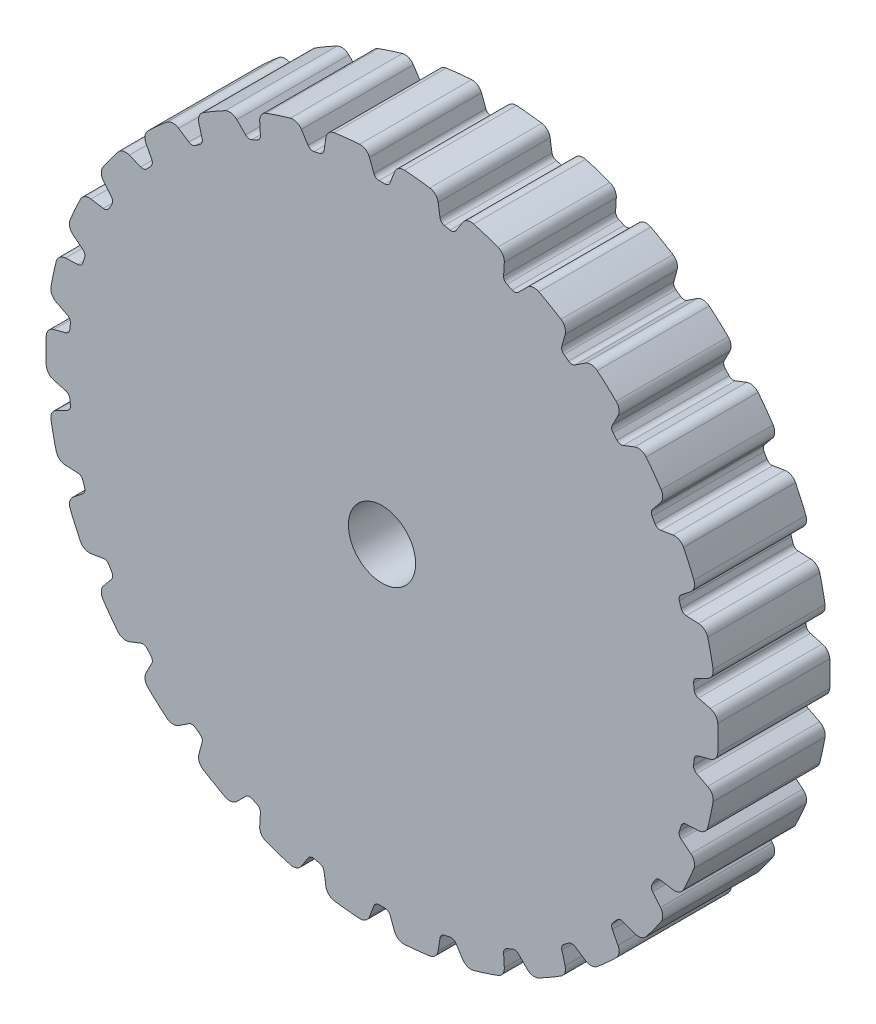
SolidWorks part; units mm, degrees
ref_plane "Front Plane" through (0, 0, 0) normal (0, 0, 1) x (1, 0, 0)
ref_plane "Top Plane" through (0, 0, 0) normal (0, 1, 0) x (1, 0, 0)
ref_plane "Right Plane" through (0, 0, 0) normal (1, 0, 0) x (0, 0, -1)
sketch "Sketch1" plane through (0, 0, 0) normal (0, 0, 1) x (1, 0, 0)
  circle A1 centre (0, 0) radius 38.1
  point P1 (0, 0)
extrude "Boss-Extrude1" add sketch "Sketch1" along normal blind 12.7
sketch "Sketch2" plane through (0, 0, 12.7) normal (0, 0, 1) x (1, 0, 0)
  circle A0 centre (0, 0) radius 3.81
extrude "Cut-Extrude1" cut sketch "Sketch2" against normal through all
sketch "Sketch3" plane through (0, 0, 12.7) normal (0, 0, 1) x (1, 0, 0)
  line L0 (0, 0) -> (0, 44.7155) construction
  line L1 (-1.4169, 37.2795) -> (-0.9223, 35.9705)
  line L2 (-0.3283, 35.56) -> (0.3283, 35.56)
  line L3 (1.4169, 37.2795) -> (0.9223, 35.9705)
  line L4 (7.0723, 34.8512) -> (7.7144, 34.7147)
  line L5 (9.1368, 36.1703) -> (8.3808, 34.9928)
  line L6 (6.3649, 36.7594) -> (6.5766, 35.3763)
  line L7 (14.1637, 32.6192) -> (14.7634, 32.3522)
  line L8 (16.4573, 33.4802) -> (15.4731, 32.4856)
  line L9 (13.8686, 34.6328) -> (13.788, 33.2358)
  line L10 (20.6361, 28.9616) -> (21.1672, 28.5757)
  line L11 (23.0586, 29.3269) -> (21.8891, 28.5587)
  line L12 (20.7661, 30.9926) -> (20.3968, 29.6429)
  line L13 (26.2066, 24.0382) -> (26.6459, 23.5503)
  line L14 (28.6521, 23.8919) -> (27.3484, 23.3836)
  line L15 (26.756, 25.9978) -> (26.1142, 24.7544)
  line L16 (30.6317, 18.0643) -> (30.96, 17.4957)
  line L17 (32.9934, 17.4127) -> (31.6125, 17.1866)
  line L18 (31.5765, 19.8668) -> (30.6903, 18.784)
  line L19 (33.7181, 11.3008) -> (33.921, 10.6765)
  line L20 (35.8927, 10.1725) -> (34.495, 10.2384)
  line L21 (35.0171, 12.8675) -> (33.925, 11.9926)
  line L22 (35.3309, 4.0435) -> (35.3995, 3.3906)
  line L23 (37.2234, 2.4877) -> (35.8699, 2.8427)
  line L24 (36.9272, 5.3059) -> (35.6771, 4.6772)
  line L25 (35.3995, -3.3906) -> (35.3309, -4.0435)
  line L26 (36.9272, -5.3059) -> (35.6771, -4.6772)
  line L27 (37.2234, -2.4877) -> (35.8699, -2.8427)
  line L28 (33.921, -10.6765) -> (33.7181, -11.3008)
  line L29 (35.0171, -12.8675) -> (33.925, -11.9926)
  line L30 (35.8927, -10.1725) -> (34.495, -10.2384)
  line L31 (30.96, -17.4957) -> (30.6317, -18.0643)
  line L32 (31.5765, -19.8668) -> (30.6903, -18.784)
  line L33 (32.9934, -17.4127) -> (31.6125, -17.1866)
  line L34 (26.6459, -23.5503) -> (26.2066, -24.0382)
  line L35 (26.756, -25.9978) -> (26.1142, -24.7544)
  line L36 (28.6521, -23.8919) -> (27.3484, -23.3836)
  line L37 (21.1672, -28.5757) -> (20.6361, -28.9616)
  line L38 (20.7661, -30.9926) -> (20.3968, -29.6429)
  line L39 (23.0586, -29.3269) -> (21.8891, -28.5587)
  line L40 (14.7634, -32.3522) -> (14.1637, -32.6192)
  line L41 (13.8686, -34.6328) -> (13.788, -33.2358)
  line L42 (16.4573, -33.4802) -> (15.4731, -32.4856)
  line L43 (7.7144, -34.7147) -> (7.0723, -34.8512)
  line L44 (6.3649, -36.7594) -> (6.5766, -35.3763)
  line L45 (9.1368, -36.1703) -> (8.3808, -34.9928)
  line L46 (0.3283, -35.56) -> (-0.3283, -35.56)
  line L47 (-1.4169, -37.2795) -> (-0.9223, -35.9705)
  line L48 (1.4169, -37.2795) -> (0.9223, -35.9705)
  line L49 (-7.0723, -34.8512) -> (-7.7144, -34.7147)
  line L50 (-9.1368, -36.1703) -> (-8.3808, -34.9928)
  line L51 (-6.3649, -36.7594) -> (-6.5766, -35.3763)
  line L52 (-14.1637, -32.6192) -> (-14.7634, -32.3522)
  line L53 (-16.4573, -33.4802) -> (-15.4731, -32.4856)
  line L54 (-13.8686, -34.6328) -> (-13.788, -33.2358)
  line L55 (-20.6361, -28.9616) -> (-21.1672, -28.5757)
  line L56 (-23.0586, -29.3269) -> (-21.8891, -28.5587)
  line L57 (-20.7661, -30.9926) -> (-20.3968, -29.6429)
  line L58 (-26.2066, -24.0382) -> (-26.6459, -23.5503)
  line L59 (-28.6521, -23.8919) -> (-27.3484, -23.3836)
  line L60 (-26.756, -25.9978) -> (-26.1142, -24.7544)
  line L61 (-30.6317, -18.0643) -> (-30.96, -17.4957)
  line L62 (-32.9934, -17.4127) -> (-31.6125, -17.1866)
  line L63 (-31.5765, -19.8668) -> (-30.6903, -18.784)
  line L64 (-33.7181, -11.3008) -> (-33.921, -10.6765)
  line L65 (-35.8927, -10.1725) -> (-34.495, -10.2384)
  line L66 (-35.0171, -12.8675) -> (-33.925, -11.9926)
  line L67 (-35.3309, -4.0435) -> (-35.3995, -3.3906)
  line L68 (-37.2234, -2.4877) -> (-35.8699, -2.8427)
  line L69 (-36.9272, -5.3059) -> (-35.6771, -4.6772)
  line L70 (-35.3995, 3.3906) -> (-35.3309, 4.0435)
  line L71 (-36.9272, 5.3059) -> (-35.6771, 4.6772)
  line L72 (-37.2234, 2.4877) -> (-35.8699, 2.8427)
  line L73 (-33.921, 10.6765) -> (-33.7181, 11.3008)
  line L74 (-35.0171, 12.8675) -> (-33.925, 11.9926)
  line L75 (-35.8927, 10.1725) -> (-34.495, 10.2384)
  line L76 (-30.96, 17.4957) -> (-30.6317, 18.0643)
  line L77 (-31.5765, 19.8668) -> (-30.6903, 18.784)
  line L78 (-32.9934, 17.4127) -> (-31.6125, 17.1866)
  line L79 (-26.6459, 23.5503) -> (-26.2066, 24.0382)
  line L80 (-26.756, 25.9978) -> (-26.1142, 24.7544)
  line L81 (-28.6521, 23.8919) -> (-27.3484, 23.3836)
  line L82 (-21.1672, 28.5757) -> (-20.6361, 28.9616)
  line L83 (-20.7661, 30.9926) -> (-20.3968, 29.6429)
  line L84 (-23.0586, 29.3269) -> (-21.8891, 28.5587)
  line L85 (-14.7634, 32.3522) -> (-14.1637, 32.6192)
  line L86 (-13.8686, 34.6328) -> (-13.788, 33.2358)
  line L87 (-16.4573, 33.4802) -> (-15.4731, 32.4856)
  line L88 (-7.7144, 34.7147) -> (-7.0723, 34.8512)
  line L89 (-6.3649, 36.7594) -> (-6.5766, 35.3763)
  line L90 (-9.1368, 36.1703) -> (-8.3808, 34.9928)
  circle A0 centre (0, 0) radius 38.1 construction
  arc A1 (-0.9223, 35.9705) -> (-0.3283, 35.56) centre (-0.3283, 36.195) ccw
  arc A2 (-2.54, 38.0152) -> (2.54, 38.0152) centre (0, 0) cw
  arc A3 (-1.4169, 37.2795) -> (-2.54, 38.0152) centre (-2.4834, 36.8765) ccw
  arc A4 (0.9223, 35.9705) -> (0.3283, 35.56) centre (0.3283, 36.195) cw
  arc A5 (1.4169, 37.2795) -> (2.54, 38.0152) centre (2.4834, 36.8765) cw
  arc A6 (8.3808, 34.9928) -> (7.7144, 34.7147) centre (7.8465, 35.3358) cw
  arc A7 (9.1368, 36.1703) -> (10.3883, 36.6564) centre (10.0962, 35.5543) cw
  arc A8 (5.4193, 37.7126) -> (10.3883, 36.6564) centre (0, 0) cw
  arc A9 (6.3649, 36.7594) -> (5.4193, 37.7126) centre (5.2379, 36.587) ccw
  arc A10 (6.5766, 35.3763) -> (7.0723, 34.8512) centre (7.2043, 35.4723) ccw
  arc A11 (15.4731, 32.4856) -> (14.7634, 32.3522) centre (15.0217, 32.9323) cw
  arc A12 (16.4573, 33.4802) -> (17.7826, 33.6955) centre (17.2678, 32.6782) cw
  arc A13 (13.1418, 35.7618) -> (17.7826, 33.6955) centre (0, 0) cw
  arc A14 (13.8686, 34.6328) -> (13.1418, 35.7618) centre (12.7303, 34.6984) ccw
  arc A15 (13.788, 33.2358) -> (14.1637, 32.6192) centre (14.422, 33.1993) ccw
  arc A16 (21.8891, 28.5587) -> (21.1672, 28.5757) centre (21.5405, 29.0894) cw
  arc A17 (23.0586, 29.3269) -> (24.3997, 29.262) centre (23.6846, 28.374) cw
  arc A18 (20.2899, 32.2479) -> (24.3997, 29.262) centre (0, 0) cw
  arc A19 (20.7661, 30.9926) -> (20.2899, 32.2479) centre (19.6663, 31.2934) ccw
  arc A20 (20.3968, 29.6429) -> (20.6361, 28.9616) centre (21.0093, 29.4753) ccw
  arc A21 (27.3484, 23.3836) -> (26.6459, 23.5503) centre (27.1178, 23.9752) cw
  arc A22 (28.6521, 23.8919) -> (29.9504, 23.5496) centre (29.0663, 22.8296) cw
  arc A23 (26.5512, 27.3247) -> (29.9504, 23.5496) centre (0, 0) cw
  arc A24 (26.756, 25.9978) -> (26.5512, 27.3247) centre (25.7428, 26.5207) ccw
  arc A25 (26.1142, 24.7544) -> (26.2066, 24.0382) centre (26.6785, 24.4631) ccw
  arc A26 (31.6125, 17.1866) -> (30.96, 17.4957) centre (31.5099, 17.8132) cw
  arc A27 (32.9934, 17.4127) -> (34.1922, 16.8079) centre (33.1777, 16.2875) cw
  arc A28 (31.6522, 21.2073) -> (34.1922, 16.8079) centre (0, 0) cw
  arc A29 (31.5765, 19.8668) -> (31.6522, 21.2073) centre (30.6942, 20.589) ccw
  arc A30 (30.6903, 18.784) -> (30.6317, 18.0643) centre (31.1817, 18.3818) ccw
  arc A31 (34.495, 10.2384) -> (33.921, 10.6765) centre (34.5249, 10.8727) cw
  arc A32 (35.8927, 10.1725) -> (36.9395, 9.3317) centre (35.839, 9.0336) cw
  arc A33 (35.3697, 14.163) -> (36.9395, 9.3317) centre (0, 0) cw
  arc A34 (35.0171, 12.8675) -> (35.3697, 14.163) centre (34.3042, 13.7574) ccw
  arc A35 (33.925, 11.9926) -> (33.7181, 11.3008) centre (34.3221, 11.4971) ccw
  arc A36 (35.8699, 2.8427) -> (35.3995, 3.3906) centre (36.031, 3.4569) cw
  arc A37 (37.2234, 2.4877) -> (38.0725, 1.4476) centre (36.934, 1.3848) cw
  arc A38 (37.5415, 6.4998) -> (38.0725, 1.4476) centre (0, 0) cw
  arc A39 (36.9272, 5.3059) -> (37.5415, 6.4998) centre (36.4149, 6.3245) ccw
  arc A40 (35.6771, 4.6772) -> (35.3309, 4.0435) centre (35.9624, 4.1099) ccw
  arc A41 (35.6771, -4.6772) -> (35.3309, -4.0435) centre (35.9624, -4.1099) cw
  arc A42 (36.9272, -5.3059) -> (37.5415, -6.4998) centre (36.4149, -6.3245) cw
  arc A43 (38.0725, -1.4476) -> (37.5415, -6.4998) centre (0, 0) cw
  arc A44 (37.2234, -2.4877) -> (38.0725, -1.4476) centre (36.934, -1.3848) ccw
  arc A45 (35.8699, -2.8427) -> (35.3995, -3.3906) centre (36.031, -3.4569) ccw
  arc A46 (33.925, -11.9926) -> (33.7181, -11.3008) centre (34.3221, -11.4971) cw
  arc A47 (35.0171, -12.8675) -> (35.3697, -14.163) centre (34.3042, -13.7574) cw
  arc A48 (36.9395, -9.3317) -> (35.3697, -14.163) centre (0, 0) cw
  arc A49 (35.8927, -10.1725) -> (36.9395, -9.3317) centre (35.839, -9.0336) ccw
  arc A50 (34.495, -10.2384) -> (33.921, -10.6765) centre (34.5249, -10.8727) ccw
  arc A51 (30.6903, -18.784) -> (30.6317, -18.0643) centre (31.1817, -18.3818) cw
  arc A52 (31.5765, -19.8668) -> (31.6522, -21.2073) centre (30.6942, -20.589) cw
  arc A53 (34.1922, -16.8079) -> (31.6522, -21.2073) centre (0, 0) cw
  arc A54 (32.9934, -17.4127) -> (34.1922, -16.8079) centre (33.1777, -16.2875) ccw
  arc A55 (31.6125, -17.1866) -> (30.96, -17.4957) centre (31.5099, -17.8132) ccw
  arc A56 (26.1142, -24.7544) -> (26.2066, -24.0382) centre (26.6785, -24.4631) cw
  arc A57 (26.756, -25.9978) -> (26.5512, -27.3247) centre (25.7428, -26.5207) cw
  arc A58 (29.9504, -23.5496) -> (26.5512, -27.3247) centre (0, 0) cw
  arc A59 (28.6521, -23.8919) -> (29.9504, -23.5496) centre (29.0663, -22.8296) ccw
  arc A60 (27.3484, -23.3836) -> (26.6459, -23.5503) centre (27.1178, -23.9752) ccw
  arc A61 (20.3968, -29.6429) -> (20.6361, -28.9616) centre (21.0093, -29.4753) cw
  arc A62 (20.7661, -30.9926) -> (20.2899, -32.2479) centre (19.6663, -31.2934) cw
  arc A63 (24.3997, -29.262) -> (20.2899, -32.2479) centre (0, 0) cw
  arc A64 (23.0586, -29.3269) -> (24.3997, -29.262) centre (23.6846, -28.374) ccw
  arc A65 (21.8891, -28.5587) -> (21.1672, -28.5757) centre (21.5405, -29.0894) ccw
  arc A66 (13.788, -33.2358) -> (14.1637, -32.6192) centre (14.422, -33.1993) cw
  arc A67 (13.8686, -34.6328) -> (13.1418, -35.7618) centre (12.7303, -34.6984) cw
  arc A68 (17.7826, -33.6955) -> (13.1418, -35.7618) centre (0, 0) cw
  arc A69 (16.4573, -33.4802) -> (17.7826, -33.6955) centre (17.2678, -32.6782) ccw
  arc A70 (15.4731, -32.4856) -> (14.7634, -32.3522) centre (15.0217, -32.9323) ccw
  arc A71 (6.5766, -35.3763) -> (7.0723, -34.8512) centre (7.2043, -35.4723) cw
  arc A72 (6.3649, -36.7594) -> (5.4193, -37.7126) centre (5.2379, -36.587) cw
  arc A73 (10.3883, -36.6564) -> (5.4193, -37.7126) centre (0, 0) cw
  arc A74 (9.1368, -36.1703) -> (10.3883, -36.6564) centre (10.0962, -35.5543) ccw
  arc A75 (8.3808, -34.9928) -> (7.7144, -34.7147) centre (7.8465, -35.3358) ccw
  arc A76 (-0.9223, -35.9705) -> (-0.3283, -35.56) centre (-0.3283, -36.195) cw
  arc A77 (-1.4169, -37.2795) -> (-2.54, -38.0152) centre (-2.4834, -36.8765) cw
  arc A78 (2.54, -38.0152) -> (-2.54, -38.0152) centre (0, 0) cw
  arc A79 (1.4169, -37.2795) -> (2.54, -38.0152) centre (2.4834, -36.8765) ccw
  arc A80 (0.9223, -35.9705) -> (0.3283, -35.56) centre (0.3283, -36.195) ccw
  arc A81 (-8.3808, -34.9928) -> (-7.7144, -34.7147) centre (-7.8465, -35.3358) cw
  arc A82 (-9.1368, -36.1703) -> (-10.3883, -36.6564) centre (-10.0962, -35.5543) cw
  arc A83 (-5.4193, -37.7126) -> (-10.3883, -36.6564) centre (0, 0) cw
  arc A84 (-6.3649, -36.7594) -> (-5.4193, -37.7126) centre (-5.2379, -36.587) ccw
  arc A85 (-6.5766, -35.3763) -> (-7.0723, -34.8512) centre (-7.2043, -35.4723) ccw
  arc A86 (-15.4731, -32.4856) -> (-14.7634, -32.3522) centre (-15.0217, -32.9323) cw
  arc A87 (-16.4573, -33.4802) -> (-17.7826, -33.6955) centre (-17.2678, -32.6782) cw
  arc A88 (-13.1418, -35.7618) -> (-17.7826, -33.6955) centre (0, 0) cw
  arc A89 (-13.8686, -34.6328) -> (-13.1418, -35.7618) centre (-12.7303, -34.6984) ccw
  arc A90 (-13.788, -33.2358) -> (-14.1637, -32.6192) centre (-14.422, -33.1993) ccw
  arc A91 (-21.8891, -28.5587) -> (-21.1672, -28.5757) centre (-21.5405, -29.0894) cw
  arc A92 (-23.0586, -29.3269) -> (-24.3997, -29.262) centre (-23.6846, -28.374) cw
  arc A93 (-20.2899, -32.2479) -> (-24.3997, -29.262) centre (0, 0) cw
  arc A94 (-20.7661, -30.9926) -> (-20.2899, -32.2479) centre (-19.6663, -31.2934) ccw
  arc A95 (-20.3968, -29.6429) -> (-20.6361, -28.9616) centre (-21.0093, -29.4753) ccw
  arc A96 (-27.3484, -23.3836) -> (-26.6459, -23.5503) centre (-27.1178, -23.9752) cw
  arc A97 (-28.6521, -23.8919) -> (-29.9504, -23.5496) centre (-29.0663, -22.8296) cw
  arc A98 (-26.5512, -27.3247) -> (-29.9504, -23.5496) centre (0, 0) cw
  arc A99 (-26.756, -25.9978) -> (-26.5512, -27.3247) centre (-25.7428, -26.5207) ccw
  arc A100 (-26.1142, -24.7544) -> (-26.2066, -24.0382) centre (-26.6785, -24.4631) ccw
  arc A101 (-31.6125, -17.1866) -> (-30.96, -17.4957) centre (-31.5099, -17.8132) cw
  arc A102 (-32.9934, -17.4127) -> (-34.1922, -16.8079) centre (-33.1777, -16.2875) cw
  arc A103 (-31.6522, -21.2073) -> (-34.1922, -16.8079) centre (0, 0) cw
  arc A104 (-31.5765, -19.8668) -> (-31.6522, -21.2073) centre (-30.6942, -20.589) ccw
  arc A105 (-30.6903, -18.784) -> (-30.6317, -18.0643) centre (-31.1817, -18.3818) ccw
  arc A106 (-34.495, -10.2384) -> (-33.921, -10.6765) centre (-34.5249, -10.8727) cw
  arc A107 (-35.8927, -10.1725) -> (-36.9395, -9.3317) centre (-35.839, -9.0336) cw
  arc A108 (-35.3697, -14.163) -> (-36.9395, -9.3317) centre (0, 0) cw
  arc A109 (-35.0171, -12.8675) -> (-35.3697, -14.163) centre (-34.3042, -13.7574) ccw
  arc A110 (-33.925, -11.9926) -> (-33.7181, -11.3008) centre (-34.3221, -11.4971) ccw
  arc A111 (-35.8699, -2.8427) -> (-35.3995, -3.3906) centre (-36.031, -3.4569) cw
  arc A112 (-37.2234, -2.4877) -> (-38.0725, -1.4476) centre (-36.934, -1.3848) cw
  arc A113 (-37.5415, -6.4998) -> (-38.0725, -1.4476) centre (0, 0) cw
  arc A114 (-36.9272, -5.3059) -> (-37.5415, -6.4998) centre (-36.4149, -6.3245) ccw
  arc A115 (-35.6771, -4.6772) -> (-35.3309, -4.0435) centre (-35.9624, -4.1099) ccw
  arc A116 (-35.6771, 4.6772) -> (-35.3309, 4.0435) centre (-35.9624, 4.1099) cw
  arc A117 (-36.9272, 5.3059) -> (-37.5415, 6.4998) centre (-36.4149, 6.3245) cw
  arc A118 (-38.0725, 1.4476) -> (-37.5415, 6.4998) centre (0, 0) cw
  arc A119 (-37.2234, 2.4877) -> (-38.0725, 1.4476) centre (-36.934, 1.3848) ccw
  arc A120 (-35.8699, 2.8427) -> (-35.3995, 3.3906) centre (-36.031, 3.4569) ccw
  arc A121 (-33.925, 11.9926) -> (-33.7181, 11.3008) centre (-34.3221, 11.4971) cw
  arc A122 (-35.0171, 12.8675) -> (-35.3697, 14.163) centre (-34.3042, 13.7574) cw
  arc A123 (-36.9395, 9.3317) -> (-35.3697, 14.163) centre (0, 0) cw
  arc A124 (-35.8927, 10.1725) -> (-36.9395, 9.3317) centre (-35.839, 9.0336) ccw
  arc A125 (-34.495, 10.2384) -> (-33.921, 10.6765) centre (-34.5249, 10.8727) ccw
  arc A126 (-30.6903, 18.784) -> (-30.6317, 18.0643) centre (-31.1817, 18.3818) cw
  arc A127 (-31.5765, 19.8668) -> (-31.6522, 21.2073) centre (-30.6942, 20.589) cw
  arc A128 (-34.1922, 16.8079) -> (-31.6522, 21.2073) centre (0, 0) cw
  arc A129 (-32.9934, 17.4127) -> (-34.1922, 16.8079) centre (-33.1777, 16.2875) ccw
  arc A130 (-31.6125, 17.1866) -> (-30.96, 17.4957) centre (-31.5099, 17.8132) ccw
  arc A131 (-26.1142, 24.7544) -> (-26.2066, 24.0382) centre (-26.6785, 24.4631) cw
  arc A132 (-26.756, 25.9978) -> (-26.5512, 27.3247) centre (-25.7428, 26.5207) cw
  arc A133 (-29.9504, 23.5496) -> (-26.5512, 27.3247) centre (0, 0) cw
  arc A134 (-28.6521, 23.8919) -> (-29.9504, 23.5496) centre (-29.0663, 22.8296) ccw
  arc A135 (-27.3484, 23.3836) -> (-26.6459, 23.5503) centre (-27.1178, 23.9752) ccw
  arc A136 (-20.3968, 29.6429) -> (-20.6361, 28.9616) centre (-21.0093, 29.4753) cw
  arc A137 (-20.7661, 30.9926) -> (-20.2899, 32.2479) centre (-19.6663, 31.2934) cw
  arc A138 (-24.3997, 29.262) -> (-20.2899, 32.2479) centre (0, 0) cw
  arc A139 (-23.0586, 29.3269) -> (-24.3997, 29.262) centre (-23.6846, 28.374) ccw
  arc A140 (-21.8891, 28.5587) -> (-21.1672, 28.5757) centre (-21.5405, 29.0894) ccw
  arc A141 (-13.788, 33.2358) -> (-14.1637, 32.6192) centre (-14.422, 33.1993) cw
  arc A142 (-13.8686, 34.6328) -> (-13.1418, 35.7618) centre (-12.7303, 34.6984) cw
  arc A143 (-17.7826, 33.6955) -> (-13.1418, 35.7618) centre (0, 0) cw
  arc A144 (-16.4573, 33.4802) -> (-17.7826, 33.6955) centre (-17.2678, 32.6782) ccw
  arc A145 (-15.4731, 32.4856) -> (-14.7634, 32.3522) centre (-15.0217, 32.9323) ccw
  arc A146 (-6.5766, 35.3763) -> (-7.0723, 34.8512) centre (-7.2043, 35.4723) cw
  arc A147 (-6.3649, 36.7594) -> (-5.4193, 37.7126) centre (-5.2379, 36.587) cw
  arc A148 (-10.3883, 36.6564) -> (-5.4193, 37.7126) centre (0, 0) cw
  arc A149 (-9.1368, 36.1703) -> (-10.3883, 36.6564) centre (-10.0962, 35.5543) ccw
  arc A150 (-8.3808, 34.9928) -> (-7.7144, 34.7147) centre (-7.8465, 35.3358) ccw
  point P3 (0, 35.56)
  point P4 (0, 38.1)
  point P15 (0, 35.56)
  point P371 (0, 0)
  dimension "D2" = 0.635
  dimension "D1" = 2.54
  dimension "D3" = 2.54
  dimension "D4" = 30
extrude "Cut-Extrude2" cut sketch "Sketch3" against normal through all
